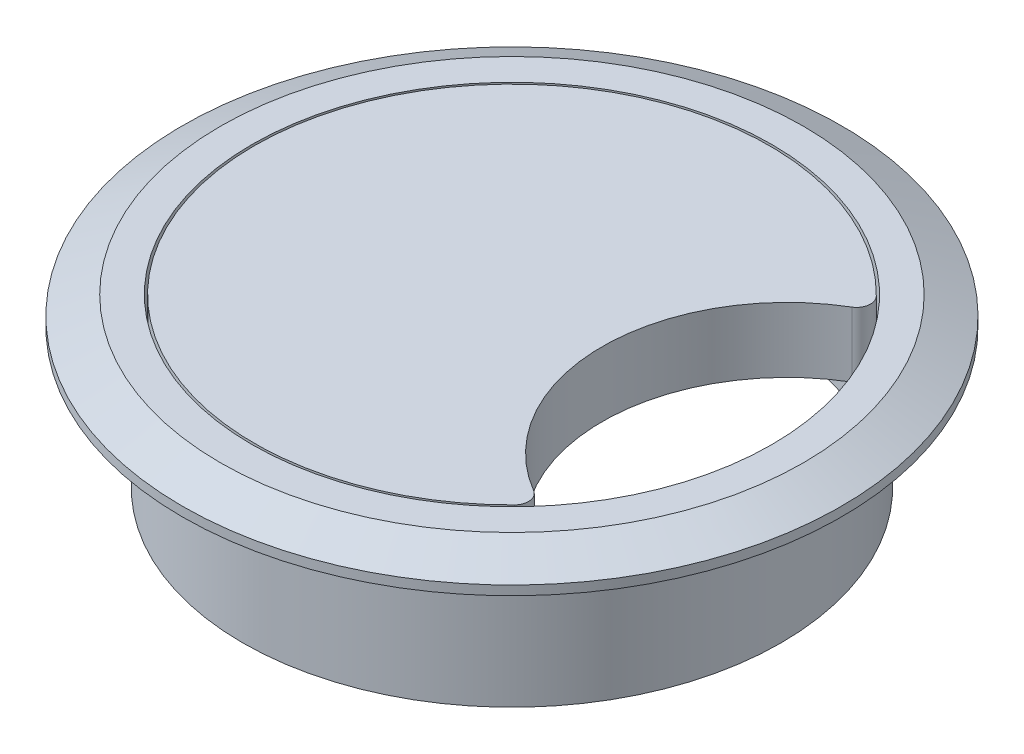
SolidWorks part; units mm, degrees
material "Жесткий ПВХ"
ref_plane "Спереди" through (0, 0, 0) normal (0, 0, 1) x (1, 0, 0)
ref_plane "Сверху" through (0, 0, 0) normal (0, 1, 0) x (1, 0, 0)
ref_plane "Справа" through (0, 0, 0) normal (1, 0, 0) x (0, 0, -1)
sketch "Эскиз1" plane through (0, 0, 0) normal (0, 1, 0) x (1, 0, 0)
  circle A0 centre (0, 0) radius 35.5
  circle A1 centre (0, 0) radius 28
  dimension "D1" = 71
  dimension "D2" = 56
extrude "Бобышка-Вытянуть1" add sketch "Эскиз1" along normal blind 3
chamfer "Фаска1" distance 2 angle 64 1 edges at (0, 3, 35.5)
sketch "Эскиз2" plane through (0, 0, 0) normal (0, -1, 0) x (1, 0, 0)
  circle A0 centre (0, 0) radius 29
  circle A1 centre (0, 0) radius 28
  dimension "D1" = 58
extrude "Бобышка-Вытянуть2" add sketch "Эскиз2" along normal blind 15
sketch "Эскиз3" plane through (0, 3, 0) normal (0, 1, 0) x (1, 0, 0)
  line L0 (0, 0) -> (57.7345, 0) construction
  arc A0 (21.1192, 18.009) -> (21.1192, -18.009) centre (0, 0) ccw
  arc A1 (21.1192, 18.009) -> (21.1192, -18.009) centre (29.6411, 0) ccw
extrude "Бобышка-Вытянуть3" add sketch "Эскиз3" against normal blind 7 separate body
fillet "Скругление1" radius 1.5 2 edges at (21.1192, -0.5, -18.009) (21.1192, -0.5, 18.009)
